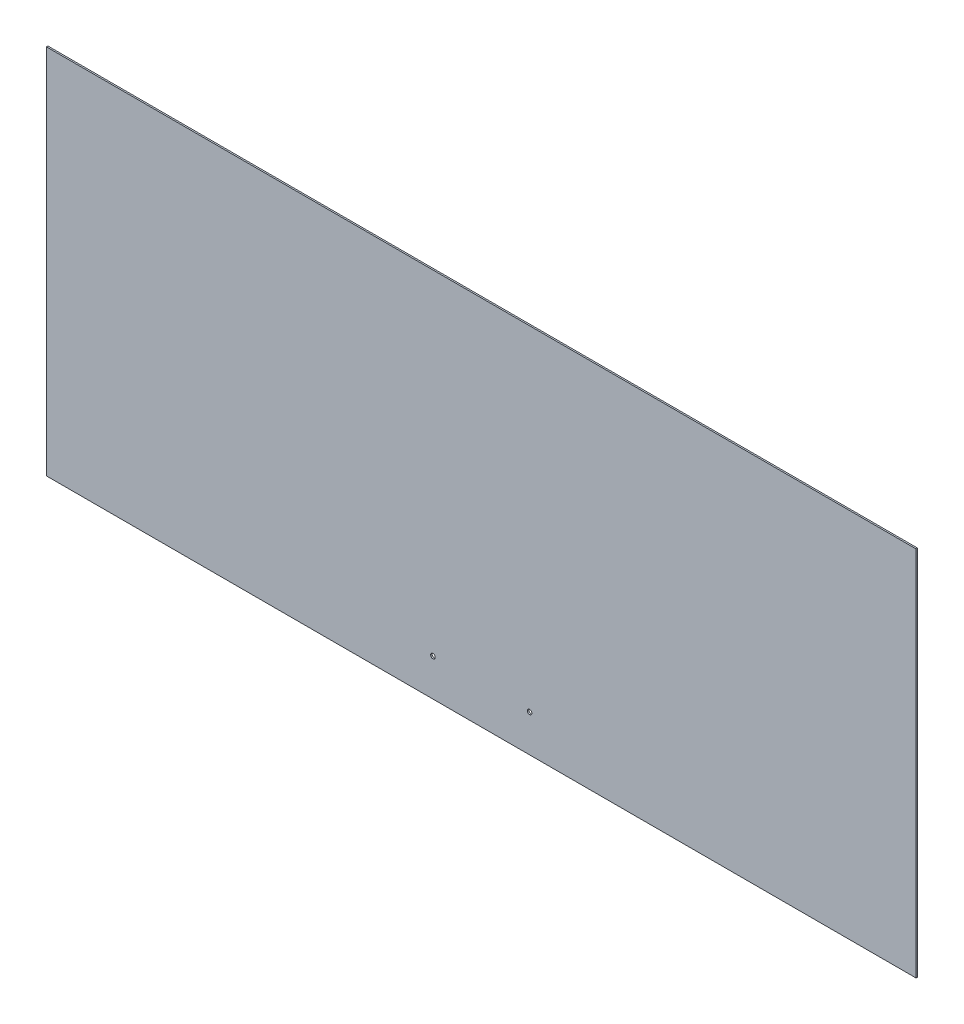
SolidWorks part; units mm, degrees
ref_plane "Front Plane" through (0, 0, 0) normal (0, 0, 1) x (1, 0, 0)
ref_plane "Top Plane" through (0, 0, 0) normal (0, 1, 0) x (1, 0, 0)
ref_plane "Right Plane" through (0, 0, 0) normal (1, 0, 0) x (0, 0, -1)
sketch "Sketch1" plane through (0, 0, 0) normal (0, 0, 1) x (1, 0, 0)
  line L1 (0, 0) -> (1170, 0)
  line L2 (0, 0) -> (0, -500)
  line L3 (0, -500) -> (1170, -500)
  line L4 (1170, 0) -> (1170, -500)
  dimension "D1" = 500
  dimension "D2" = 1170
extrude "Boss-Extrude1" add sketch "Sketch1" along normal blind 2
sketch "Sketch2" plane through (0, 0, 2) normal (0, 0, 1) x (1, 0, 0)
  line L0 (585, 0) -> (585, -500) construction
  line L1 (1170, 0) -> (0, 0) construction
  line L2 (0, -500) -> (1170, -500) construction
  line L3 (520, -450) -> (650, -450) construction
  circle A0 centre (520, -450) radius 3.1
  circle A1 centre (650, -450) radius 3.1
  point P10 (0, 0)
  dimension "D2" = 6.2
  dimension "D1" = 50
  dimension "D3" = 130
extrude "Cut-Extrude1" cut sketch "Sketch2" against normal through all
